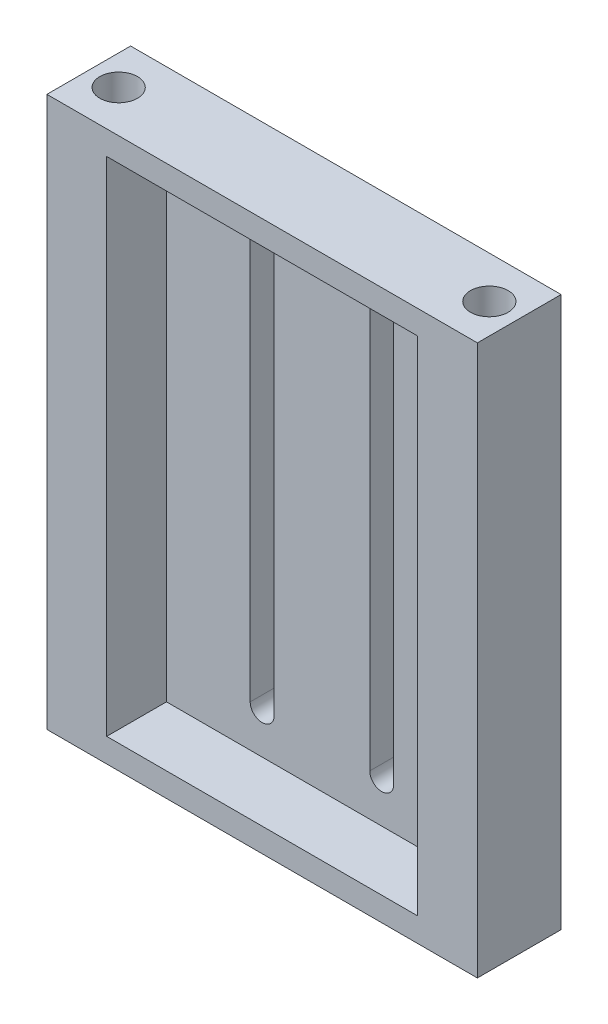
SolidWorks part; units mm, degrees
ref_plane "Front" through (0, 0, 0) normal (0, 0, 1) x (1, 0, 0)
ref_plane "Top" through (0, 0, 0) normal (0, 1, 0) x (1, 0, 0)
ref_plane "Right" through (0, 0, 0) normal (1, 0, 0) x (0, 0, -1)
sketch "Sketch1" plane through (0, 0, 0) normal (0, 0, 1) x (1, 0, 0)
  line L1 (-18, 23) -> (18, 23)
  line L2 (-18, 23) -> (-18, -23)
  line L3 (-18, -23) -> (18, -23)
  line L4 (18, 23) -> (18, -23)
  line L5 (-18, 23) -> (18, -23) construction
  line L6 (-18, -23) -> (18, 23) construction
  point P0 (0, 0)
  dimension "D1" = 36
  dimension "D2" = 46
extrude "Boss-Extrude1" add sketch "Sketch1" along normal blind 2
sketch "Sketch2" plane through (0, 0, 2) normal (0, 0, 1) x (1, 0, 0)
  line L1 (-18, 23) -> (18, 23)
  line L2 (-18, 23) -> (-18, -23)
  line L3 (-18, -23) -> (18, -23)
  line L4 (18, 23) -> (18, -23)
  line L5 (-18, 23) -> (18, -23) construction
  line L6 (-18, -23) -> (18, 23) construction
  line L7 (-13, 21) -> (13, 21)
  line L8 (-13, 21) -> (-13, -21)
  line L9 (-13, -21) -> (13, -21)
  line L10 (13, 21) -> (13, -21)
  line L11 (-13, 21) -> (13, -21) construction
  line L12 (-13, -21) -> (13, 21) construction
  point P0 (0, 0)
  point P7 (0, 0)
  dimension "D1" = 26
  dimension "D2" = 42
extrude "Boss-Extrude2" add sketch "Sketch2" along normal blind 5
sketch "Sketch3" plane through (0, 23, 0) normal (0, 1, 0) x (1, 0, 0)
  line L0 (-18, -7) -> (-18, 0) construction
  line L1 (0, 2.8551) -> (0, -9.681) construction
  line L2 (18, -7) -> (-18, -7) construction
  circle A0 centre (-15.5, -3.5) radius 1.575
  circle A1 centre (15.5, -3.5) radius 1.575
  dimension "D1" = 3.15
  dimension "D2" = 2.5
  dimension "D3" = 3.5
extrude "Cut-Extrude1" cut sketch "Sketch3" against normal through all
sketch "Sketch4" plane through (0, 0, 0) normal (0, 0, -1) x (-1, 0, 0)
  line L0 (-5, 17.5) -> (-5, -17.5) construction
  line L1 (-4, 17.5) -> (-4, -17.5)
  line L2 (-6, 17.5) -> (-6, -17.5)
  line L3 (0, 7.5703) -> (0, -12.2611) construction
  line L4 (5, 17.5) -> (5, -17.5) construction
  line L5 (4, 17.5) -> (4, -17.5)
  line L6 (6, 17.5) -> (6, -17.5)
  arc A0 (-4, 17.5) -> (-6, 17.5) centre (-5, 17.5) ccw
  arc A1 (-6, -17.5) -> (-4, -17.5) centre (-5, -17.5) ccw
  arc A2 (4, 17.5) -> (6, 17.5) centre (5, 17.5) cw
  arc A3 (6, -17.5) -> (4, -17.5) centre (5, -17.5) cw
  point P2 (-5, 0)
  point P12 (5, 0)
  dimension "D2" = 1
  dimension "D1" = 35
  dimension "D3" = 5
extrude "Cut-Extrude2" cut sketch "Sketch4" against normal blind 2
